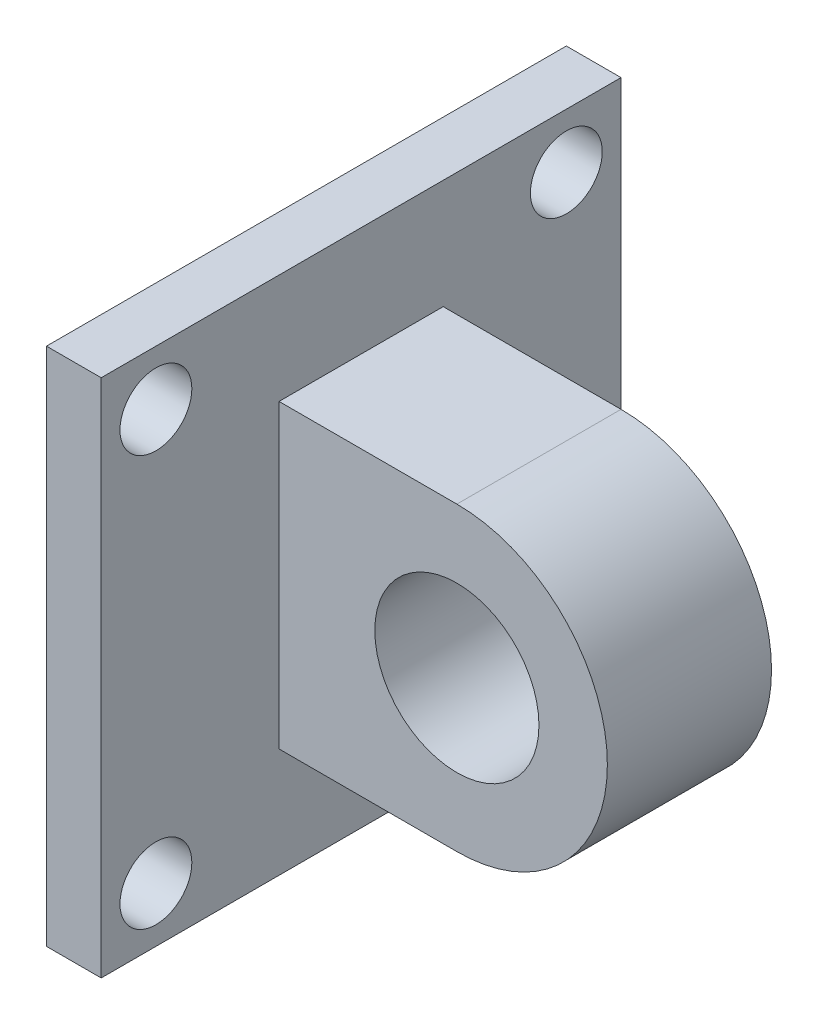
SolidWorks part; units mm, degrees
material "Cast Carbon Steel"
ref_plane "Front Plane" through (0, 0, 0) normal (0, 0, 1) x (1, 0, 0)
ref_plane "Top Plane" through (0, 0, 0) normal (0, 1, 0) x (1, 0, 0)
ref_plane "Right Plane" through (0, 0, 0) normal (1, 0, 0) x (0, 0, -1)
ref_plane "Plane4" through (25.4, 0, 0) normal (1, 0, 0) x (0, 0, -1)
sketch "Sketch1" plane through (25.4, 0, 0) normal (1, 0, 0) x (0, 0, -1)
  line L0 (-120.65, 120.65) -> (-120.65, -120.65)
  line L1 (-120.65, -120.65) -> (120.65, -120.65)
  line L2 (120.65, -120.65) -> (120.65, 120.65)
  line L3 (120.65, 120.65) -> (-120.65, 120.65)
extrude "Boss-Extrude1" add sketch "Sketch1" against normal blind 25.4
ref_plane "Plane5" through (0, 0, 38.1) normal (0, 0, 1) x (1, 0, 0)
sketch "Sketch2" plane through (0, 0, 38.1) normal (0, 0, 1) x (1, 0, 0)
  line L0 (25.4, 69.85) -> (25.4, -69.85)
  line L1 (25.4, -69.85) -> (107.95, -69.85)
  line L2 (107.95, 69.85) -> (25.4, 69.85)
  arc A0 (107.95, -69.85) -> (107.95, 69.85) centre (107.95, 0) ccw
extrude "Boss-Extrude2" add sketch "Sketch2" against normal blind 76.2
hole_wizard "Hole1" positions "Sketch4" profile "Sketch3" legacy
sketch "Sketch4" plane through (0, 0, -38.1) normal (0, 0, -1) x (-1, 0, 0)
  point P0 (-107.95, 0)
sketch "Sketch3" plane through (107.95, 0, -38.1) normal (1, 0, 0) x (0, 1, 0)
  line L0 (0, 0) -> (0, 158.75)
  line L1 (0, 158.75) -> (38.1, 158.75)
  line L2 (38.1, 158.75) -> (38.1, 0)
  line L3 (38.1, 0) -> (0, 0)
  line L4 (0, 110) -> (0, -10) construction
  dimension "Diameter" = 76.2
  dimension "Depth" = 158.75
hole_wizard "Hole2" positions "Sketch6" profile "Sketch5" legacy
sketch "Sketch6" plane through (0, 0, 0) normal (-1, 0, 0) x (0, 0, 1)
  point P0 (-95.25, -95.25)
  point P1 (-95.25, 95.25)
  point P2 (95.25, -95.25)
  point P3 (95.25, 95.25)
sketch "Sketch5" plane through (0, -95.25, -95.25) normal (0, 1, 0) x (0, 0, 1)
  line L0 (0, 0) -> (0, 177.8)
  line L1 (0, 177.8) -> (16.6751, 177.8)
  line L2 (16.6751, 177.8) -> (16.6751, 0)
  line L3 (16.6751, 0) -> (0, 0)
  line L4 (0, 110) -> (0, -10) construction
  dimension "Diameter" = 33.3502
  dimension "Depth" = 177.8
